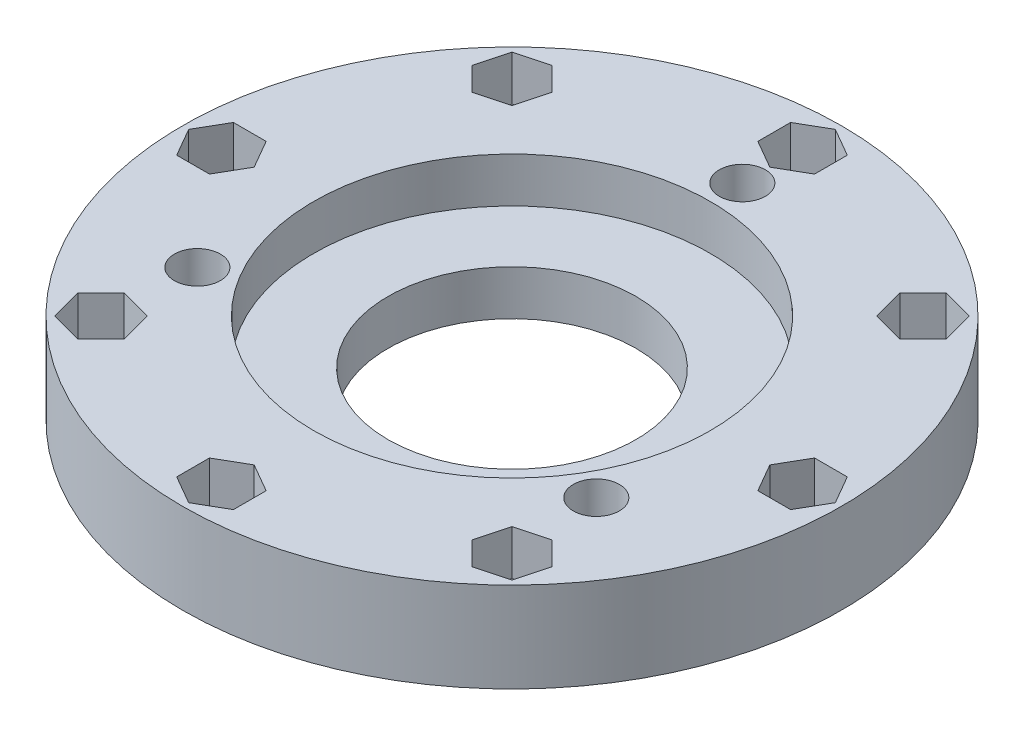
SolidWorks part; units mm, degrees
ref_plane "Front Plane" through (0, 0, 0) normal (0, 0, 1) x (1, 0, 0)
ref_plane "Top Plane" through (0, 0, 0) normal (0, 1, 0) x (1, 0, 0)
ref_plane "Right Plane" through (0, 0, 0) normal (1, 0, 0) x (0, 0, -1)
sketch "Sketch1" plane through (0, 0, 0) normal (0, 1, 0) x (1, 0, 0)
  circle A0 centre (0, 0) radius 46.5
  circle A1 centre (0, 0) radius 32.5 construction
  circle A2 centre (0, 32.5) radius 2.5
  circle A3 centre (28.1458, -16.25) radius 2.5
  circle A4 centre (-28.1458, -16.25) radius 2.5
  circle A5 centre (0, 0) radius 17.5
  point P13 (0, 0)
  dimension "D1" = 93
  dimension "D2" = 65
  dimension "D3" = 5
  dimension "D5" = 35
  dimension "D4" = 3
extrude "Boss-Extrude1" add sketch "Sketch1" along normal blind 12.7
sketch "Sketch2" plane through (0, 12.7, 0) normal (0, 1, 0) x (1, 0, 0)
  circle A0 centre (0, 0) radius 28
  dimension "D1" = 56
extrude "Cut-Extrude1" cut sketch "Sketch2" against normal blind 6.35
sketch "Sketch3" plane through (0, 12.7, 0) normal (0, 1, 0) x (1, 0, 0)
  line L0 (0, 41) -> (0, 0) construction
  circle A0 centre (0, 0) radius 41 construction
  circle A1 centre (0, 41) radius 2.5
  circle A2 centre (28.9914, 28.9914) radius 2.5
  circle A3 centre (41, 0) radius 2.5
  circle A4 centre (28.9914, -28.9914) radius 2.5
  circle A5 centre (0, -41) radius 2.5
  circle A6 centre (-28.9914, -28.9914) radius 2.5
  circle A7 centre (-41, 0) radius 2.5
  circle A8 centre (-28.9914, 28.9914) radius 2.5
  point P21 (0, 0)
  dimension "D1" = 82
  dimension "D2" = 5
  dimension "D3" = 8
extrude "Cut-Extrude2" cut sketch "Sketch3" against normal blind 6.35
sketch "Sketch4" plane through (0, 12.7, 0) normal (0, 1, 0) x (1, 0, 0)
  line L0 (0, 45.6188) -> (-4, 43.3094)
  line L1 (-4, 43.3094) -> (-4, 38.6906)
  line L2 (-4, 38.6906) -> (0, 36.3812)
  line L3 (0, 36.3812) -> (4, 38.6906)
  line L4 (4, 38.6906) -> (4, 43.3094)
  line L5 (4, 43.3094) -> (0, 45.6188)
  line L6 (0, 45.6188) -> (0, 36.3812) construction
  line L7 (33.4528, 27.7959) -> (32.2574, 32.2574)
  line L8 (32.2574, 32.2574) -> (27.7959, 33.4528)
  line L9 (27.7959, 33.4528) -> (24.53, 30.1868)
  line L10 (24.53, 30.1868) -> (25.7254, 25.7254)
  line L11 (25.7254, 25.7254) -> (30.1868, 24.53)
  line L12 (30.1868, 24.53) -> (33.4528, 27.7959)
  line L13 (43.3094, -4) -> (45.6188, 0)
  line L14 (45.6188, 0) -> (43.3094, 4)
  line L15 (43.3094, 4) -> (38.6906, 4)
  line L16 (38.6906, 4) -> (36.3812, 0)
  line L17 (36.3812, 0) -> (38.6906, -4)
  line L18 (38.6906, -4) -> (43.3094, -4)
  line L19 (27.7959, -33.4528) -> (32.2574, -32.2574)
  line L20 (32.2574, -32.2574) -> (33.4528, -27.7959)
  line L21 (33.4528, -27.7959) -> (30.1868, -24.53)
  line L22 (30.1868, -24.53) -> (25.7254, -25.7254)
  line L23 (25.7254, -25.7254) -> (24.53, -30.1868)
  line L24 (24.53, -30.1868) -> (27.7959, -33.4528)
  line L25 (-4, -43.3094) -> (0, -45.6188)
  line L26 (0, -45.6188) -> (4, -43.3094)
  line L27 (4, -43.3094) -> (4, -38.6906)
  line L28 (4, -38.6906) -> (0, -36.3812)
  line L29 (0, -36.3812) -> (-4, -38.6906)
  line L30 (-4, -38.6906) -> (-4, -43.3094)
  line L31 (-33.4528, -27.7959) -> (-32.2574, -32.2574)
  line L32 (-32.2574, -32.2574) -> (-27.7959, -33.4528)
  line L33 (-27.7959, -33.4528) -> (-24.53, -30.1868)
  line L34 (-24.53, -30.1868) -> (-25.7254, -25.7254)
  line L35 (-25.7254, -25.7254) -> (-30.1868, -24.53)
  line L36 (-30.1868, -24.53) -> (-33.4528, -27.7959)
  line L37 (-43.3094, 4) -> (-45.6188, 0)
  line L38 (-45.6188, 0) -> (-43.3094, -4)
  line L39 (-43.3094, -4) -> (-38.6906, -4)
  line L40 (-38.6906, -4) -> (-36.3812, 0)
  line L41 (-36.3812, 0) -> (-38.6906, 4)
  line L42 (-38.6906, 4) -> (-43.3094, 4)
  line L43 (-27.7959, 33.4528) -> (-32.2574, 32.2574)
  line L44 (-32.2574, 32.2574) -> (-33.4528, 27.7959)
  line L45 (-33.4528, 27.7959) -> (-30.1868, 24.53)
  line L46 (-30.1868, 24.53) -> (-25.7254, 25.7254)
  line L47 (-25.7254, 25.7254) -> (-24.53, 30.1868)
  line L48 (-24.53, 30.1868) -> (-27.7959, 33.4528)
  line L49 (-30.1868, 24.53) -> (-27.7959, 33.4528) construction
  circle A0 centre (0, 32.5) radius 3.25
  circle A1 centre (28.1458, -16.25) radius 3.25
  circle A2 centre (-28.1458, -16.25) radius 3.25
  circle A3 centre (-28.1458, -16.25) radius 2.5 construction
  circle A4 centre (0, 41) radius 2.5 construction
  circle A5 centre (0, 41) radius 2.5 construction
  circle A6 centre (-28.9914, 28.9914) radius 2.5 construction
  circle A7 centre (-28.9914, 28.9914) radius 2.5 construction
  point P9 (0, 0)
  point P64 (0, 0)
  dimension "D1" = 3
  dimension "8" = 6.5
  dimension "D2" = 8
  dimension "D3" = 120
  dimension "D4" = 120
  dimension "D5" = 8
extrude "Cut-Extrude3" cut sketch "Sketch4" against normal blind 6.35
sketch "Sketch5" plane through (0, 12.7, 0) normal (0, 1, 0) x (1, 0, 0)
  line L2 (0, 36.3812) -> (0, 45.6188) construction
  circle A0 centre (0, 41) radius 2.5 construction
  circle A1 centre (0, 32.5) radius 2.5 construction
  circle A2 centre (0, 32.5) radius 2.5 construction
  point P2 (0, 0)
  dimension "D1" = 5
